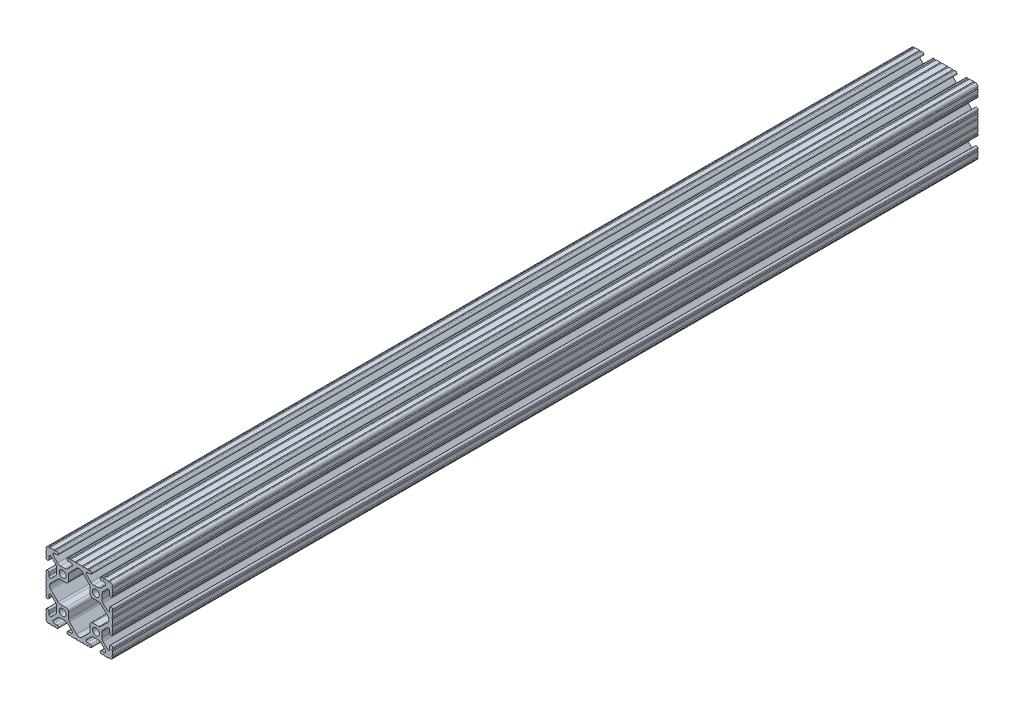
SolidWorks part; units mm, degrees
material "6063-T6"
ref_plane "Front Plane" through (0, 0, 0) normal (0, 0, 1) x (1, 0, 0)
ref_plane "Top Plane" through (0, 0, 0) normal (0, 1, 0) x (1, 0, 0)
ref_plane "Right Plane" through (0, 0, 0) normal (1, 0, 0) x (0, 0, -1)
sketch "Sketch1" plane through (0, 0, 0) normal (0, 0, 1) x (1, 0, 0)
  line L0 (-10.4013, 8.1915) -> (-14.7306, 8.1915)
  line L1 (-16.2932, 7.5443) -> (-21.772, 2.0655)
  line L2 (-21.772, -2.0655) -> (-16.2932, -7.5443)
  line L3 (-14.7306, -8.1915) -> (-10.4013, -8.1915)
  line L4 (-8.1915, -10.4013) -> (-8.1915, -14.7306)
  line L5 (-7.5443, -16.2932) -> (-2.0655, -21.772)
  line L6 (2.0655, -21.772) -> (7.5443, -16.2932)
  line L7 (8.1915, -14.7306) -> (8.1915, -10.4013)
  line L8 (10.4013, -8.1915) -> (14.7306, -8.1915)
  line L9 (16.2932, -7.5443) -> (21.772, -2.0655)
  line L10 (21.772, 2.0655) -> (16.2932, 7.5443)
  line L11 (14.7306, 8.1915) -> (10.4013, 8.1915)
  line L12 (8.1915, 10.4013) -> (8.1915, 14.7306)
  line L13 (7.5443, 16.2932) -> (2.0655, 21.772)
  line L14 (-2.0655, 21.772) -> (-7.5443, 16.2932)
  line L15 (-8.1915, 14.7306) -> (-8.1915, 10.4013)
  line L16 (-2.1336, -25.4) -> (2.1336, -25.4)
  line L17 (3.1496, -25.4) -> (6.3754, -25.4)
  line L18 (7.3914, -25.4) -> (8.3439, -25.4)
  line L19 (8.3439, -23.1902) -> (6.2252, -23.1902)
  line L20 (5.5068, -21.4558) -> (8.8241, -18.1384)
  line L21 (11.0692, -17.2085) -> (14.3308, -17.2085)
  line L22 (16.5759, -18.1384) -> (19.8932, -21.4558)
  line L23 (19.1748, -23.1902) -> (17.0561, -23.1902)
  line L24 (17.0561, -25.4) -> (18.0086, -25.4)
  line L25 (19.0246, -25.4) -> (22.2504, -25.4)
  line L26 (23.2664, -25.4) -> (23.2918, -25.4)
  line L27 (25.4, -23.2918) -> (25.4, -23.2664)
  line L28 (25.4, -22.2504) -> (25.4, -19.0246)
  line L29 (25.4, -18.0086) -> (25.4, -17.0561)
  line L30 (23.1902, -17.0561) -> (23.1902, -19.1748)
  line L31 (21.4558, -19.8932) -> (18.1384, -16.5759)
  line L32 (17.2085, -14.3308) -> (17.2085, -11.0692)
  line L33 (18.1384, -8.8241) -> (21.4558, -5.5068)
  line L34 (23.1902, -6.2252) -> (23.1902, -8.3439)
  line L35 (25.4, -8.3439) -> (25.4, -7.3914)
  line L36 (25.4, -6.3754) -> (25.4, -3.1496)
  line L37 (25.4, -2.1336) -> (25.4, 2.1336)
  line L38 (25.4, 3.1496) -> (25.4, 6.3754)
  line L39 (25.4, 7.3914) -> (25.4, 8.3439)
  line L40 (23.1902, 8.3439) -> (23.1902, 6.2252)
  line L41 (21.4558, 5.5068) -> (18.1384, 8.8241)
  line L42 (17.2085, 11.0692) -> (17.2085, 14.3308)
  line L43 (18.1384, 16.5759) -> (21.4558, 19.8932)
  line L44 (23.1902, 19.1748) -> (23.1902, 17.0561)
  line L45 (25.4, 17.0561) -> (25.4, 18.0086)
  line L46 (25.4, 19.0246) -> (25.4, 22.2504)
  line L47 (25.4, 23.2664) -> (25.4, 23.2918)
  line L48 (23.2918, 25.4) -> (23.2664, 25.4)
  line L49 (22.2504, 25.4) -> (19.0246, 25.4)
  line L50 (18.0086, 25.4) -> (17.0561, 25.4)
  line L51 (17.0561, 23.1902) -> (19.1748, 23.1902)
  line L52 (19.8932, 21.4558) -> (16.5759, 18.1384)
  line L53 (14.3308, 17.2085) -> (11.0692, 17.2085)
  line L54 (8.8241, 18.1384) -> (5.5068, 21.4558)
  line L55 (6.2252, 23.1902) -> (8.3439, 23.1902)
  line L56 (8.3439, 25.4) -> (7.3914, 25.4)
  line L57 (6.3754, 25.4) -> (3.1496, 25.4)
  line L58 (2.1336, 25.4) -> (-2.1336, 25.4)
  line L59 (-3.1496, 25.4) -> (-6.3754, 25.4)
  line L60 (-7.3914, 25.4) -> (-8.3439, 25.4)
  line L61 (-8.3439, 23.1902) -> (-6.2252, 23.1902)
  line L62 (-5.5068, 21.4558) -> (-8.8241, 18.1384)
  line L63 (-11.0692, 17.2085) -> (-14.3308, 17.2085)
  line L64 (-16.5759, 18.1384) -> (-19.8932, 21.4558)
  line L65 (-19.1748, 23.1902) -> (-17.0561, 23.1902)
  line L66 (-17.0561, 25.4) -> (-18.0086, 25.4)
  line L67 (-19.0246, 25.4) -> (-22.2504, 25.4)
  line L68 (-23.2664, 25.4) -> (-23.2918, 25.4)
  line L69 (-25.4, 23.2918) -> (-25.4, 23.2664)
  line L70 (-25.4, 22.2504) -> (-25.4, 19.0246)
  line L71 (-25.4, 18.0086) -> (-25.4, 17.0561)
  line L72 (-23.1902, 17.0561) -> (-23.1902, 19.1748)
  line L73 (-21.4558, 19.8932) -> (-18.1384, 16.5759)
  line L74 (-17.2085, 14.3308) -> (-17.2085, 11.0692)
  line L75 (-18.1384, 8.8241) -> (-21.4558, 5.5068)
  line L76 (-23.1902, 6.2252) -> (-23.1902, 8.3439)
  line L77 (-25.4, 8.3439) -> (-25.4, 7.3914)
  line L78 (-25.4, 6.3754) -> (-25.4, 3.1496)
  line L79 (-25.4, 2.1336) -> (-25.4, -2.1336)
  line L80 (-25.4, -3.1496) -> (-25.4, -6.3754)
  line L81 (-25.4, -7.3914) -> (-25.4, -8.3439)
  line L82 (-23.1902, -8.3439) -> (-23.1902, -6.2252)
  line L83 (-21.4558, -5.5068) -> (-18.1384, -8.8241)
  line L84 (-17.2085, -11.0692) -> (-17.2085, -14.3308)
  line L85 (-18.1384, -16.5759) -> (-21.4558, -19.8932)
  line L86 (-23.1902, -19.1748) -> (-23.1902, -17.0561)
  line L87 (-25.4, -17.0561) -> (-25.4, -18.0086)
  line L88 (-25.4, -19.0246) -> (-25.4, -22.2504)
  line L89 (-25.4, -23.2664) -> (-25.4, -23.2918)
  line L90 (-23.2918, -25.4) -> (-23.2664, -25.4)
  line L91 (-22.2504, -25.4) -> (-19.0246, -25.4)
  line L92 (-18.0086, -25.4) -> (-17.0561, -25.4)
  line L93 (-17.0561, -23.1902) -> (-19.1748, -23.1902)
  line L94 (-19.8932, -21.4558) -> (-16.5759, -18.1384)
  line L95 (-14.3308, -17.2085) -> (-11.0692, -17.2085)
  line L96 (-8.8241, -18.1384) -> (-5.5068, -21.4558)
  line L97 (-6.2252, -23.1902) -> (-8.3439, -23.1902)
  line L98 (-8.3439, -25.4) -> (-7.3914, -25.4)
  line L99 (-6.3754, -25.4) -> (-3.1496, -25.4)
  arc A0 (-14.7306, 8.1915) -> (-16.2932, 7.5443) centre (-14.7306, 5.9817) ccw
  arc A1 (-21.772, 2.0655) -> (-21.772, -2.0655) centre (-19.7065, 0) ccw
  arc A2 (-16.2932, -7.5443) -> (-14.7306, -8.1915) centre (-14.7306, -5.9817) ccw
  arc A3 (-8.1915, -10.4013) -> (-10.4013, -8.1915) centre (-10.4013, -10.4013) ccw
  arc A4 (-8.1915, -14.7306) -> (-7.5443, -16.2932) centre (-5.9817, -14.7306) ccw
  arc A5 (-2.0655, -21.772) -> (2.0655, -21.772) centre (0, -19.7065) ccw
  arc A6 (7.5443, -16.2932) -> (8.1915, -14.7306) centre (5.9817, -14.7306) ccw
  arc A7 (10.4013, -8.1915) -> (8.1915, -10.4013) centre (10.4013, -10.4013) ccw
  arc A8 (14.7306, -8.1915) -> (16.2932, -7.5443) centre (14.7306, -5.9817) ccw
  arc A9 (21.772, -2.0655) -> (21.772, 2.0655) centre (19.7065, 0) ccw
  arc A10 (16.2932, 7.5443) -> (14.7306, 8.1915) centre (14.7306, 5.9817) ccw
  arc A11 (8.1915, 10.4013) -> (10.4013, 8.1915) centre (10.4013, 10.4013) ccw
  arc A12 (8.1915, 14.7306) -> (7.5443, 16.2932) centre (5.9817, 14.7306) ccw
  arc A13 (2.0655, 21.772) -> (-2.0655, 21.772) centre (0, 19.7065) ccw
  arc A14 (-7.5443, 16.2932) -> (-8.1915, 14.7306) centre (-5.9817, 14.7306) ccw
  arc A15 (-10.4013, 8.1915) -> (-8.1915, 10.4013) centre (-10.4013, 10.4013) ccw
  arc A16 (-2.1336, -25.4) -> (-3.1496, -25.4) centre (-2.6416, -25.4) ccw
  arc A17 (3.1496, -25.4) -> (2.1336, -25.4) centre (2.6416, -25.4) ccw
  arc A18 (7.3914, -25.4) -> (6.3754, -25.4) centre (6.8834, -25.4) ccw
  arc A19 (8.3439, -25.4) -> (8.3439, -23.1902) centre (8.3439, -24.2951) ccw
  arc A20 (5.5068, -21.4558) -> (6.2252, -23.1902) centre (6.2252, -22.1742) ccw
  arc A21 (11.0692, -17.2085) -> (8.8241, -18.1384) centre (11.0692, -20.3835) ccw
  arc A22 (16.5759, -18.1384) -> (14.3308, -17.2085) centre (14.3308, -20.3835) ccw
  arc A23 (19.1748, -23.1902) -> (19.8932, -21.4558) centre (19.1748, -22.1742) ccw
  arc A24 (17.0561, -23.1902) -> (17.0561, -25.4) centre (17.0561, -24.2951) ccw
  arc A25 (19.0246, -25.4) -> (18.0086, -25.4) centre (18.5166, -25.4) ccw
  arc A26 (23.2664, -25.4) -> (22.2504, -25.4) centre (22.7584, -25.4) ccw
  arc A27 (23.2918, -25.4) -> (25.4, -23.2918) centre (23.2918, -23.2918) ccw
  arc A28 (25.4, -22.2504) -> (25.4, -23.2664) centre (25.4, -22.7584) ccw
  arc A29 (25.4, -18.0086) -> (25.4, -19.0246) centre (25.4, -18.5166) ccw
  arc A30 (25.4, -17.0561) -> (23.1902, -17.0561) centre (24.2951, -17.0561) ccw
  arc A31 (21.4558, -19.8932) -> (23.1902, -19.1748) centre (22.1742, -19.1748) ccw
  arc A32 (17.2085, -14.3308) -> (18.1384, -16.5759) centre (20.3835, -14.3308) ccw
  arc A33 (18.1384, -8.8241) -> (17.2085, -11.0692) centre (20.3835, -11.0692) ccw
  arc A34 (23.1902, -6.2252) -> (21.4558, -5.5068) centre (22.1742, -6.2252) ccw
  arc A35 (23.1902, -8.3439) -> (25.4, -8.3439) centre (24.2951, -8.3439) ccw
  arc A36 (25.4, -6.3754) -> (25.4, -7.3914) centre (25.4, -6.8834) ccw
  arc A37 (25.4, -2.1336) -> (25.4, -3.1496) centre (25.4, -2.6416) ccw
  arc A38 (25.4, 3.1496) -> (25.4, 2.1336) centre (25.4, 2.6416) ccw
  arc A39 (25.4, 7.3914) -> (25.4, 6.3754) centre (25.4, 6.8834) ccw
  arc A40 (25.4, 8.3439) -> (23.1902, 8.3439) centre (24.2951, 8.3439) ccw
  arc A41 (21.4558, 5.5068) -> (23.1902, 6.2252) centre (22.1742, 6.2252) ccw
  arc A42 (17.2085, 11.0692) -> (18.1384, 8.8241) centre (20.3835, 11.0692) ccw
  arc A43 (18.1384, 16.5759) -> (17.2085, 14.3308) centre (20.3835, 14.3308) ccw
  arc A44 (23.1902, 19.1748) -> (21.4558, 19.8932) centre (22.1742, 19.1748) ccw
  arc A45 (23.1902, 17.0561) -> (25.4, 17.0561) centre (24.2951, 17.0561) ccw
  arc A46 (25.4, 19.0246) -> (25.4, 18.0086) centre (25.4, 18.5166) ccw
  arc A47 (25.4, 23.2664) -> (25.4, 22.2504) centre (25.4, 22.7584) ccw
  arc A48 (25.4, 23.2918) -> (23.2918, 25.4) centre (23.2918, 23.2918) ccw
  arc A49 (22.2504, 25.4) -> (23.2664, 25.4) centre (22.7584, 25.4) ccw
  arc A50 (18.0086, 25.4) -> (19.0246, 25.4) centre (18.5166, 25.4) ccw
  arc A51 (17.0561, 25.4) -> (17.0561, 23.1902) centre (17.0561, 24.2951) ccw
  arc A52 (19.8932, 21.4558) -> (19.1748, 23.1902) centre (19.1748, 22.1742) ccw
  arc A53 (14.3308, 17.2085) -> (16.5759, 18.1384) centre (14.3308, 20.3835) ccw
  arc A54 (8.8241, 18.1384) -> (11.0692, 17.2085) centre (11.0692, 20.3835) ccw
  arc A55 (6.2252, 23.1902) -> (5.5068, 21.4558) centre (6.2252, 22.1742) ccw
  arc A56 (8.3439, 23.1902) -> (8.3439, 25.4) centre (8.3439, 24.2951) ccw
  arc A57 (6.3754, 25.4) -> (7.3914, 25.4) centre (6.8834, 25.4) ccw
  arc A58 (2.1336, 25.4) -> (3.1496, 25.4) centre (2.6416, 25.4) ccw
  arc A59 (-3.1496, 25.4) -> (-2.1336, 25.4) centre (-2.6416, 25.4) ccw
  arc A60 (-7.3914, 25.4) -> (-6.3754, 25.4) centre (-6.8834, 25.4) ccw
  arc A61 (-8.3439, 25.4) -> (-8.3439, 23.1902) centre (-8.3439, 24.2951) ccw
  arc A62 (-5.5068, 21.4558) -> (-6.2252, 23.1902) centre (-6.2252, 22.1742) ccw
  arc A63 (-11.0692, 17.2085) -> (-8.8241, 18.1384) centre (-11.0692, 20.3835) ccw
  arc A64 (-16.5759, 18.1384) -> (-14.3308, 17.2085) centre (-14.3308, 20.3835) ccw
  arc A65 (-19.1748, 23.1902) -> (-19.8932, 21.4558) centre (-19.1748, 22.1742) ccw
  arc A66 (-17.0561, 23.1902) -> (-17.0561, 25.4) centre (-17.0561, 24.2951) ccw
  arc A67 (-19.0246, 25.4) -> (-18.0086, 25.4) centre (-18.5166, 25.4) ccw
  arc A68 (-23.2664, 25.4) -> (-22.2504, 25.4) centre (-22.7584, 25.4) ccw
  arc A69 (-23.2918, 25.4) -> (-25.4, 23.2918) centre (-23.2918, 23.2918) ccw
  arc A70 (-25.4, 22.2504) -> (-25.4, 23.2664) centre (-25.4, 22.7584) ccw
  arc A71 (-25.4, 18.0086) -> (-25.4, 19.0246) centre (-25.4, 18.5166) ccw
  arc A72 (-25.4, 17.0561) -> (-23.1902, 17.0561) centre (-24.2951, 17.0561) ccw
  arc A73 (-21.4558, 19.8932) -> (-23.1902, 19.1748) centre (-22.1742, 19.1748) ccw
  arc A74 (-17.2085, 14.3308) -> (-18.1384, 16.5759) centre (-20.3835, 14.3308) ccw
  arc A75 (-18.1384, 8.8241) -> (-17.2085, 11.0692) centre (-20.3835, 11.0692) ccw
  arc A76 (-23.1902, 6.2252) -> (-21.4558, 5.5068) centre (-22.1742, 6.2252) ccw
  arc A77 (-23.1902, 8.3439) -> (-25.4, 8.3439) centre (-24.2951, 8.3439) ccw
  arc A78 (-25.4, 6.3754) -> (-25.4, 7.3914) centre (-25.4, 6.8834) ccw
  arc A79 (-25.4, 2.1336) -> (-25.4, 3.1496) centre (-25.4, 2.6416) ccw
  arc A80 (-25.4, -3.1496) -> (-25.4, -2.1336) centre (-25.4, -2.6416) ccw
  arc A81 (-25.4, -7.3914) -> (-25.4, -6.3754) centre (-25.4, -6.8834) ccw
  arc A82 (-25.4, -8.3439) -> (-23.1902, -8.3439) centre (-24.2951, -8.3439) ccw
  arc A83 (-21.4558, -5.5068) -> (-23.1902, -6.2252) centre (-22.1742, -6.2252) ccw
  arc A84 (-17.2085, -11.0692) -> (-18.1384, -8.8241) centre (-20.3835, -11.0692) ccw
  arc A85 (-18.1384, -16.5759) -> (-17.2085, -14.3308) centre (-20.3835, -14.3308) ccw
  arc A86 (-23.1902, -19.1748) -> (-21.4558, -19.8932) centre (-22.1742, -19.1748) ccw
  arc A87 (-23.1902, -17.0561) -> (-25.4, -17.0561) centre (-24.2951, -17.0561) ccw
  arc A88 (-25.4, -19.0246) -> (-25.4, -18.0086) centre (-25.4, -18.5166) ccw
  arc A89 (-25.4, -23.2664) -> (-25.4, -22.2504) centre (-25.4, -22.7584) ccw
  arc A90 (-25.4, -23.2918) -> (-23.2918, -25.4) centre (-23.2918, -23.2918) ccw
  arc A91 (-22.2504, -25.4) -> (-23.2664, -25.4) centre (-22.7584, -25.4) ccw
  arc A92 (-18.0086, -25.4) -> (-19.0246, -25.4) centre (-18.5166, -25.4) ccw
  arc A93 (-17.0561, -25.4) -> (-17.0561, -23.1902) centre (-17.0561, -24.2951) ccw
  arc A94 (-19.8932, -21.4558) -> (-19.1748, -23.1902) centre (-19.1748, -22.1742) ccw
  arc A95 (-14.3308, -17.2085) -> (-16.5759, -18.1384) centre (-14.3308, -20.3835) ccw
  arc A96 (-8.8241, -18.1384) -> (-11.0692, -17.2085) centre (-11.0692, -20.3835) ccw
  arc A97 (-6.2252, -23.1902) -> (-5.5068, -21.4558) centre (-6.2252, -22.1742) ccw
  arc A98 (-8.3439, -23.1902) -> (-8.3439, -25.4) centre (-8.3439, -24.2951) ccw
  arc A99 (-6.3754, -25.4) -> (-7.3914, -25.4) centre (-6.8834, -25.4) ccw
  circle A100 centre (12.7, 12.7) radius 2.6035
  circle A101 centre (12.7, -12.7) radius 2.6035
  circle A102 centre (-12.7, 12.7) radius 2.6035
  circle A103 centre (-12.7, -12.7) radius 2.6035
  dimension "D1" = 12.7
  dimension "D2" = 12.7
  dimension "D3" = 12.7
  dimension "D4" = 12.7
extrude "Extrude1" add sketch "Sketch1" along normal mid plane 660.4
